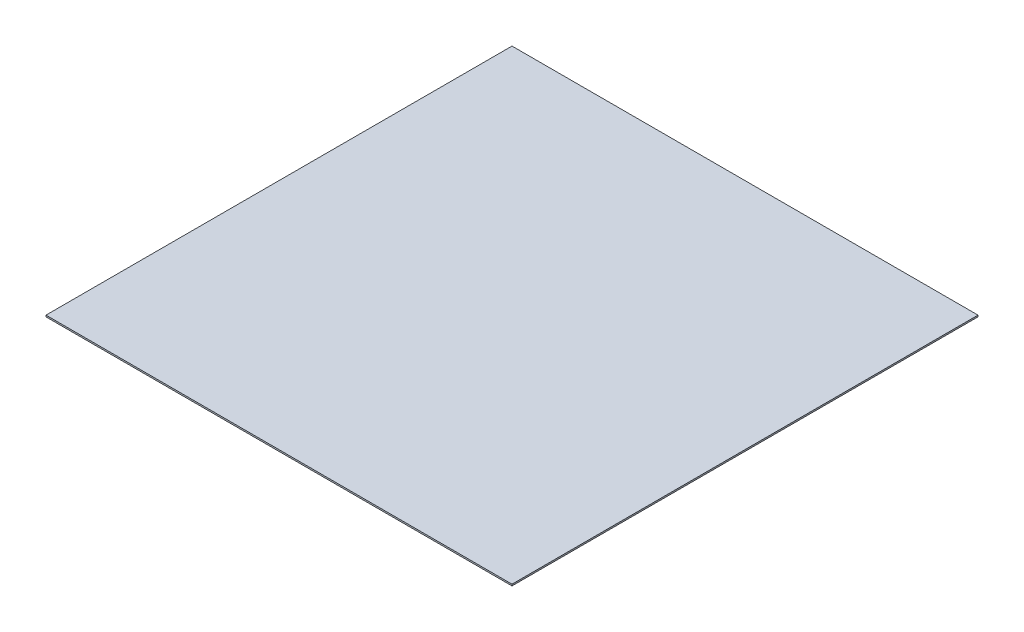
SolidWorks part; units mm, degrees
ref_plane "Спереди" through (0, 0, 0) normal (0, 0, 1) x (1, 0, 0)
ref_plane "Сверху" through (0, 0, 0) normal (0, 1, 0) x (1, 0, 0)
ref_plane "Справа" through (0, 0, 0) normal (1, 0, 0) x (0, 0, -1)
sketch "Эскиз1" plane through (0, 0, 0) normal (0, 1, 0) x (1, 0, 0)
  line L1 (0, 0) -> (3000, 0)
  line L2 (0, 0) -> (0, 3000)
  line L3 (0, 3000) -> (3000, 3000)
  line L4 (3000, 0) -> (3000, 3000)
  dimension "D1" = 3000
  dimension "D2" = 3000
extrude "Бобышка-Вытянуть1" add sketch "Эскиз1" along normal blind 10
